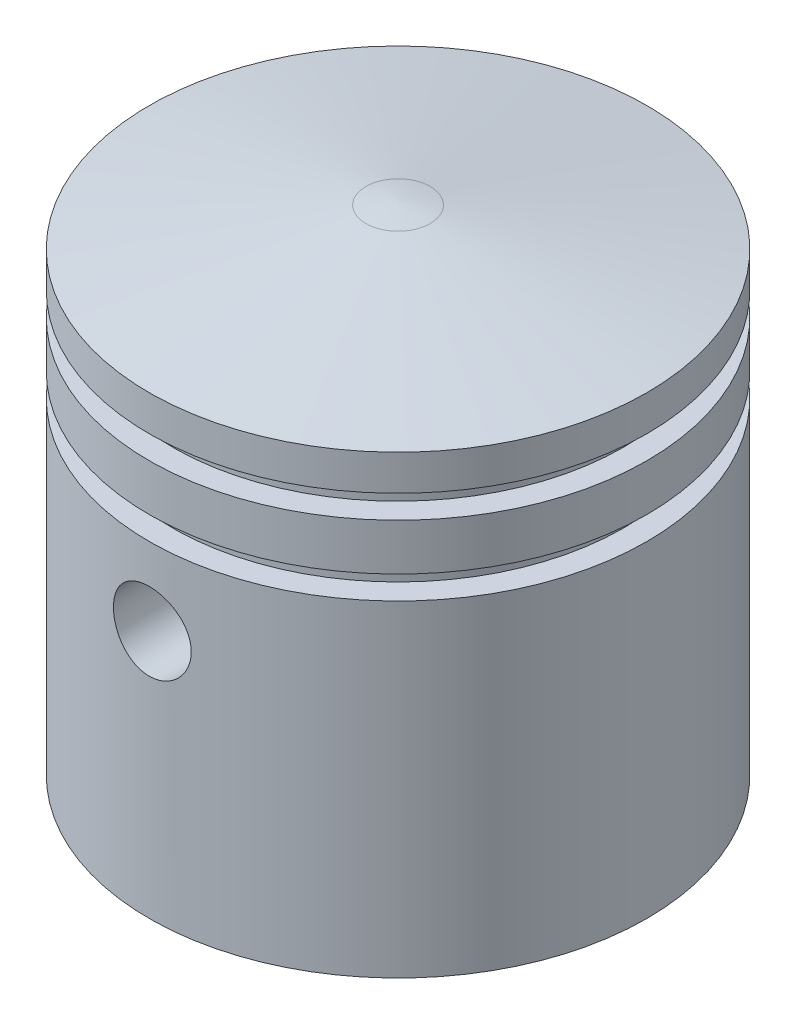
SolidWorks part; units mm, degrees
ref_plane "Front Plane" through (0, 0, 0) normal (0, 0, 1) x (1, 0, 0)
ref_plane "Top Plane" through (0, 0, 0) normal (0, 1, 0) x (1, 0, 0)
ref_plane "Right Plane" through (0, 0, 0) normal (1, 0, 0) x (0, 0, -1)
sketch "Sketch2" plane through (0, 0, 0) normal (0, 0, 1) x (1, 0, 0)
  line L2 (16, 27) -> (14.5, 27)
  line L3 (14.5, 27) -> (14.5, 25.5)
  line L4 (14.5, 25.5) -> (16, 25.5)
  line L5 (16, 25.5) -> (16, 22.5)
  line L6 (16, 22.5) -> (14.5, 22.5)
  line L7 (14.5, 22.5) -> (14.5, 21)
  line L8 (14.5, 21) -> (16, 21)
  line L9 (16, 21) -> (16, 0)
  line L10 (16, 0) -> (13, 0)
  line L11 (13, 0) -> (13, 10)
  line L12 (13, 10) -> (10, 10)
  line L13 (10, 10) -> (10, 24)
  line L14 (10, 24) -> (0, 24)
  line L16 (16, 27) -> (16, 29.2889)
  line L17 (16, 29.2889) -> (2.0673, 31.7456)
  line L18 (0, 32) -> (24.9618, 32) construction
  line L19 (0, 32) -> (0, 24)
  line L20 (0, 0) -> (0, 43.4974) construction
  arc A0 (2.0673, 31.7456) -> (0, 32) centre (-1.4056, 12.0495) ccw
  dimension "D12" = 20
  dimension "D13" = 10
  dimension "D1" = 10
  dimension "D2" = 13
  dimension "D3" = 10
  dimension "D4" = 1.5
  dimension "D5" = 3
  dimension "D6" = 1.5
  dimension "D7" = 21
  dimension "D8" = 24
  dimension "D9" = 16
  dimension "D10" = 14.5
  dimension "D11" = 32
  dimension "D14" = 29.2889
revolve "Revolve1" add sketch "Sketch2" angle 360 about L20
sketch "Sketch3" plane through (0, 0, 0) normal (0, 0, 1) x (1, 0, 0)
  circle A0 centre (0, 16) radius 2.5
  dimension "D1" = 5
  dimension "D2" = 16
extrude "Cut-Extrude1" cut sketch "Sketch3" against normal through all both and the other way through all
